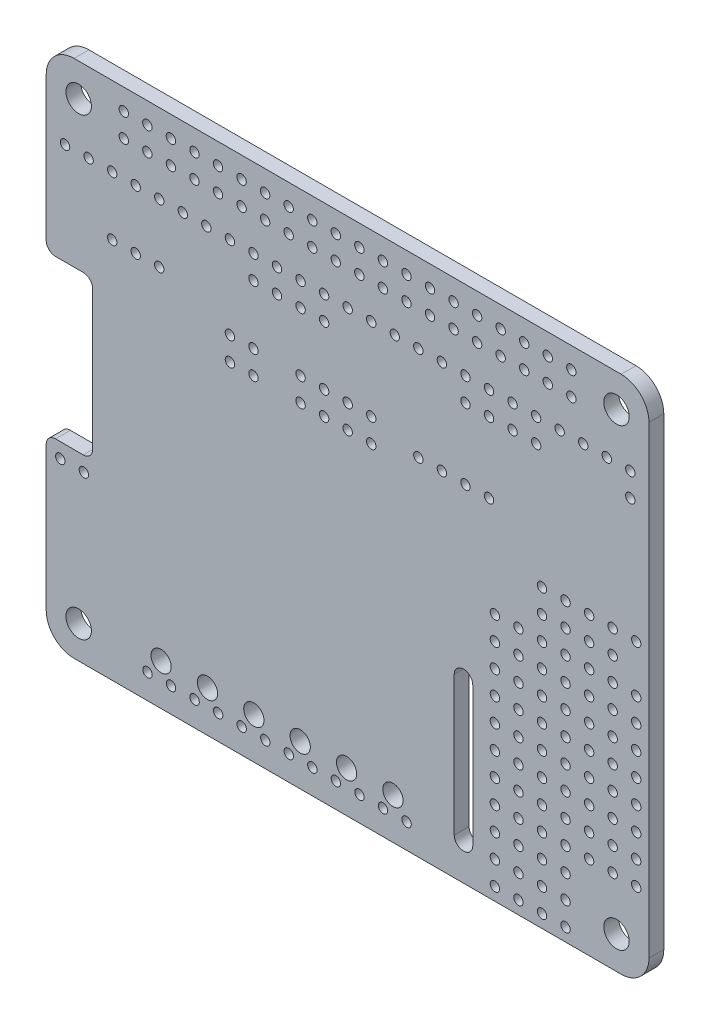
SolidWorks part; units mm, degrees
material "Polyethylene Cross-Linked"
ref_plane "Front Plane" through (0, 0, 0) normal (0, 0, 1) x (1, 0, 0)
ref_plane "Top Plane" through (0, 0, 0) normal (0, 1, 0) x (1, 0, 0)
ref_plane "Right Plane" through (0, 0, 0) normal (1, 0, 0) x (0, 0, -1)
sketch "Model" plane through (0, 0, 0) normal (0, 0, 1) x (1, 0, 0)
  line L16 (2.9997, 0) -> (62.0014, 0)
  line L17 (2.9997, 56.0332) -> (62.0014, 56.0332)
  line L18 (0, 2.9997) -> (0, 18.4988)
  line L19 (1.0008, 19.4996) -> (4.0005, 19.4996)
  line L20 (5.0013, 20.5003) -> (5.0013, 35.5329)
  line L21 (1.0008, 36.5336) -> (4.0005, 36.5336)
  line L22 (0, 37.5344) -> (0, 53.0335)
  line L23 (65.0011, 2.9997) -> (65.0011, 53.0335)
  line L24 (44.0004, 4.0005) -> (44.0004, 18.9992)
  line L25 (45.9994, 4.0005) -> (45.9994, 18.9992)
  arc A0 (0, 37.5344) -> (1.0008, 36.5336) centre (1.0008, 37.5344) ccw
  arc A1 (5.0013, 35.5329) -> (4.0005, 36.5336) centre (4.0005, 35.5329) ccw
  arc A2 (4.0005, 19.4996) -> (5.0013, 20.5003) centre (4.0005, 20.5003) ccw
  arc A3 (1.0008, 19.4996) -> (0, 18.4988) centre (1.0008, 18.4988) ccw
  arc A4 (2.9997, 56.0332) -> (0, 53.0335) centre (2.9997, 53.0335) ccw
  arc A5 (0, 2.9997) -> (2.9997, 0) centre (2.9997, 2.9997) ccw
  arc A6 (65.0011, 53.0335) -> (62.0014, 56.0332) centre (62.0014, 53.0335) ccw
  arc A7 (62.0014, 0) -> (65.0011, 2.9997) centre (62.0014, 2.9997) ccw
  arc A8 (44.0004, 4.0005) -> (45.9994, 4.0005) centre (44.9999, 4.0005) ccw
  arc A9 (45.9994, 18.9992) -> (44.0004, 18.9992) centre (44.9999, 18.9992) ccw
  circle A10 centre (8.3693, 53.7693) radius 0.508
  circle A11 centre (10.9093, 53.7693) radius 0.508
  circle A12 centre (13.4493, 53.7693) radius 0.508
  circle A13 centre (15.9893, 53.7693) radius 0.508
  circle A14 centre (18.5293, 53.7693) radius 0.508
  circle A15 centre (21.0693, 53.7693) radius 0.508
  circle A16 centre (23.6093, 53.7693) radius 0.508
  circle A17 centre (26.1493, 53.7693) radius 0.508
  circle A18 centre (28.6893, 53.7693) radius 0.508
  circle A19 centre (31.2293, 53.7693) radius 0.508
  circle A20 centre (33.7693, 53.7693) radius 0.508
  circle A21 centre (36.3093, 53.7693) radius 0.508
  circle A22 centre (38.8493, 53.7693) radius 0.508
  circle A23 centre (41.3893, 53.7693) radius 0.508
  circle A24 centre (43.9293, 53.7693) radius 0.508
  circle A25 centre (46.4693, 53.7693) radius 0.508
  circle A26 centre (49.0093, 53.7693) radius 0.508
  circle A27 centre (51.5493, 53.7693) radius 0.508
  circle A28 centre (54.0893, 53.7693) radius 0.508
  circle A29 centre (56.6293, 53.7693) radius 0.508
  circle A30 centre (10.9093, 51.2293) radius 0.508
  circle A31 centre (13.4493, 51.2293) radius 0.508
  circle A32 centre (15.9893, 51.2293) radius 0.508
  circle A33 centre (18.5293, 51.2293) radius 0.508
  circle A34 centre (21.0693, 51.2293) radius 0.508
  circle A35 centre (23.6093, 51.2293) radius 0.508
  circle A36 centre (26.1493, 51.2293) radius 0.508
  circle A37 centre (28.6893, 51.2293) radius 0.508
  circle A38 centre (31.2293, 51.2293) radius 0.508
  circle A39 centre (33.7693, 51.2293) radius 0.508
  circle A40 centre (36.3093, 51.2293) radius 0.508
  circle A41 centre (38.8493, 51.2293) radius 0.508
  circle A42 centre (41.3893, 51.2293) radius 0.508
  circle A43 centre (43.9293, 51.2293) radius 0.508
  circle A44 centre (46.4693, 51.2293) radius 0.508
  circle A45 centre (49.0093, 51.2293) radius 0.508
  circle A46 centre (51.5493, 51.2293) radius 0.508
  circle A47 centre (54.0893, 51.2293) radius 0.508
  circle A48 centre (56.6293, 51.2293) radius 0.508
  circle A49 centre (8.3693, 51.2293) radius 0.508
  circle A50 centre (3.5001, 52.4993) radius 1.3741
  circle A51 centre (61.4998, 52.4993) radius 1.3741
  circle A52 centre (61.4998, 3.5001) radius 1.3741
  circle A53 centre (3.5001, 3.5001) radius 1.3741
  circle A54 centre (2.032, 47.498) radius 0.508
  circle A55 centre (4.572, 47.498) radius 0.508
  circle A56 centre (7.112, 47.498) radius 0.508
  circle A57 centre (9.652, 47.498) radius 0.508
  circle A58 centre (12.192, 47.498) radius 0.508
  circle A59 centre (14.732, 47.498) radius 0.508
  circle A60 centre (17.272, 47.498) radius 0.508
  circle A61 centre (19.812, 47.498) radius 0.508
  circle A62 centre (22.352, 47.498) radius 0.508
  circle A63 centre (24.892, 47.498) radius 0.508
  circle A64 centre (27.432, 47.498) radius 0.508
  circle A65 centre (29.972, 47.498) radius 0.508
  circle A66 centre (32.512, 47.498) radius 0.508
  circle A67 centre (35.052, 47.498) radius 0.508
  circle A68 centre (37.592, 47.498) radius 0.508
  circle A69 centre (40.132, 47.498) radius 0.508
  circle A70 centre (42.672, 47.498) radius 0.508
  circle A71 centre (45.212, 47.498) radius 0.508
  circle A72 centre (47.752, 47.498) radius 0.508
  circle A73 centre (50.292, 47.498) radius 0.508
  circle A74 centre (52.832, 47.498) radius 0.508
  circle A75 centre (55.372, 47.498) radius 0.508
  circle A76 centre (57.912, 47.498) radius 0.508
  circle A77 centre (60.452, 47.498) radius 0.508
  circle A78 centre (62.992, 47.498) radius 0.508
  circle A79 centre (22.352, 44.958) radius 0.508
  circle A80 centre (24.892, 44.958) radius 0.508
  circle A81 centre (27.432, 44.958) radius 0.508
  circle A82 centre (29.972, 44.958) radius 0.508
  circle A83 centre (45.212, 44.958) radius 0.508
  circle A84 centre (47.752, 44.958) radius 0.508
  circle A85 centre (50.292, 44.958) radius 0.508
  circle A86 centre (52.832, 44.958) radius 0.508
  circle A87 centre (62.992, 44.958) radius 0.508
  circle A88 centre (4.064, 17.907) radius 0.508
  circle A89 centre (1.524, 17.907) radius 0.508
  circle A90 centre (38.862, 2.667) radius 0.508
  circle A91 centre (36.322, 2.667) radius 0.508
  circle A92 centre (33.782, 2.667) radius 0.508
  circle A93 centre (31.242, 2.667) radius 0.508
  circle A94 centre (28.702, 2.667) radius 0.508
  circle A95 centre (26.162, 2.667) radius 0.508
  circle A96 centre (23.622, 2.667) radius 0.508
  circle A97 centre (21.082, 2.667) radius 0.508
  circle A98 centre (18.542, 2.667) radius 0.508
  circle A99 centre (16.002, 2.667) radius 0.508
  circle A100 centre (13.462, 2.667) radius 0.508
  circle A101 centre (10.922, 2.667) radius 0.508
  circle A102 centre (37.3913, 4.445) radius 1.0922
  circle A103 centre (32.3926, 4.445) radius 1.0922
  circle A104 centre (27.3914, 4.445) radius 1.0922
  circle A105 centre (22.3926, 4.445) radius 1.0922
  circle A106 centre (17.3914, 4.445) radius 1.0922
  circle A107 centre (12.3927, 4.445) radius 1.0922
  circle A108 centre (48.387, 1.397) radius 0.508
  circle A109 centre (50.927, 1.397) radius 0.508
  circle A110 centre (53.467, 1.397) radius 0.508
  circle A111 centre (56.007, 1.397) radius 0.508
  circle A112 centre (50.927, 3.937) radius 0.508
  circle A113 centre (53.467, 3.937) radius 0.508
  circle A114 centre (56.007, 3.937) radius 0.508
  circle A115 centre (50.927, 6.477) radius 0.508
  circle A116 centre (53.467, 6.477) radius 0.508
  circle A117 centre (56.007, 6.477) radius 0.508
  circle A118 centre (50.927, 9.017) radius 0.508
  circle A119 centre (53.467, 9.017) radius 0.508
  circle A120 centre (56.007, 9.017) radius 0.508
  circle A121 centre (50.927, 11.557) radius 0.508
  circle A122 centre (53.467, 11.557) radius 0.508
  circle A123 centre (56.007, 11.557) radius 0.508
  circle A124 centre (50.927, 14.097) radius 0.508
  circle A125 centre (53.467, 14.097) radius 0.508
  circle A126 centre (56.007, 14.097) radius 0.508
  circle A127 centre (50.927, 16.637) radius 0.508
  circle A128 centre (53.467, 16.637) radius 0.508
  circle A129 centre (56.007, 16.637) radius 0.508
  circle A130 centre (50.927, 19.177) radius 0.508
  circle A131 centre (53.467, 19.177) radius 0.508
  circle A132 centre (56.007, 19.177) radius 0.508
  circle A133 centre (50.927, 21.717) radius 0.508
  circle A134 centre (53.467, 21.717) radius 0.508
  circle A135 centre (56.007, 21.717) radius 0.508
  circle A136 centre (50.927, 24.257) radius 0.508
  circle A137 centre (53.467, 24.257) radius 0.508
  circle A138 centre (56.007, 24.257) radius 0.508
  circle A139 centre (50.927, 26.797) radius 0.508
  circle A140 centre (53.467, 26.797) radius 0.508
  circle A141 centre (56.007, 26.797) radius 0.508
  circle A142 centre (48.387, 3.937) radius 0.508
  circle A143 centre (48.387, 6.477) radius 0.508
  circle A144 centre (48.387, 9.017) radius 0.508
  circle A145 centre (48.387, 11.557) radius 0.508
  circle A146 centre (48.387, 14.097) radius 0.508
  circle A147 centre (48.387, 16.637) radius 0.508
  circle A148 centre (48.387, 19.177) radius 0.508
  circle A149 centre (48.387, 21.717) radius 0.508
  circle A150 centre (48.387, 24.257) radius 0.508
  circle A151 centre (48.387, 26.797) radius 0.508
  circle A152 centre (58.547, 9.017) radius 0.508
  circle A153 centre (58.547, 11.557) radius 0.508
  circle A154 centre (58.547, 14.097) radius 0.508
  circle A155 centre (58.547, 16.637) radius 0.508
  circle A156 centre (58.547, 19.177) radius 0.508
  circle A157 centre (58.547, 21.717) radius 0.508
  circle A158 centre (58.547, 24.257) radius 0.508
  circle A159 centre (58.547, 26.797) radius 0.508
  circle A160 centre (61.087, 9.017) radius 0.508
  circle A161 centre (61.087, 11.557) radius 0.508
  circle A162 centre (61.087, 14.097) radius 0.508
  circle A163 centre (61.087, 16.637) radius 0.508
  circle A164 centre (61.087, 19.177) radius 0.508
  circle A165 centre (61.087, 21.717) radius 0.508
  circle A166 centre (61.087, 24.257) radius 0.508
  circle A167 centre (61.087, 26.797) radius 0.508
  circle A168 centre (63.627, 9.017) radius 0.508
  circle A169 centre (63.627, 11.557) radius 0.508
  circle A170 centre (63.627, 14.097) radius 0.508
  circle A171 centre (63.627, 16.637) radius 0.508
  circle A172 centre (63.627, 19.177) radius 0.508
  circle A173 centre (63.627, 21.717) radius 0.508
  circle A174 centre (63.627, 24.257) radius 0.508
  circle A175 centre (63.627, 26.797) radius 0.508
  circle A176 centre (61.087, 29.337) radius 0.508
  circle A177 centre (58.547, 29.337) radius 0.508
  circle A178 centre (56.007, 29.337) radius 0.508
  circle A179 centre (53.467, 29.337) radius 0.508
  circle A180 centre (61.087, 31.877) radius 0.508
  circle A181 centre (58.547, 31.877) radius 0.508
  circle A182 centre (56.007, 31.877) radius 0.508
  circle A183 centre (53.467, 31.877) radius 0.508
  circle A184 centre (63.627, 31.877) radius 0.508
  circle A185 centre (47.752, 37.338) radius 0.508
  circle A186 centre (45.212, 37.338) radius 0.508
  circle A188 centre (42.672, 37.338) radius 0.508
  circle A189 centre (40.132, 37.338) radius 0.508
  circle A190 centre (35.052, 38.608) radius 0.508
  circle A191 centre (35.052, 36.068) radius 0.508
  circle A192 centre (32.512, 36.068) radius 0.508
  circle A193 centre (32.512, 38.608) radius 0.508
  circle A194 centre (29.972, 38.608) radius 0.508
  circle A195 centre (29.972, 36.068) radius 0.508
  circle A196 centre (27.432, 36.068) radius 0.508
  circle A197 centre (27.432, 38.608) radius 0.508
  circle A198 centre (22.352, 38.608) radius 0.508
  circle A199 centre (22.352, 36.068) radius 0.508
  circle A200 centre (19.812, 36.068) radius 0.508
  circle A201 centre (19.812, 38.608) radius 0.508
  circle A202 centre (12.192, 41.148) radius 0.508
  circle A203 centre (9.652, 41.148) radius 0.508
  circle A204 centre (7.112, 41.148) radius 0.508
  dimension "D1" = 1.0008
  dimension "D2" = 2.9997
  dimension "D3" = 5.0013
  dimension "D7" = 1.016
  dimension "D14" = 2.7483
  dimension "D19" = 1.016
  dimension "D24" = 1.016
  dimension "D4" = 62.0014
  dimension "D5" = 19.4996
  dimension "D6" = 4
  dimension "D8" = 8.3693
  dimension "D9" = 11
  dimension "D12" = 2.54
  dimension "D13" = 2.54
  dimension "D15" = 3.5001
  dimension "D16" = 61.4998
  dimension "D17" = 3.5001
  dimension "D18" = 52.4993
  dimension "D20" = 2.032
  dimension "D21" = 2.264
  dimension "D23" = 2.54
  dimension "D25" = 8.5352
  dimension "D26" = 2.54
  dimension "D10" = 20
  dimension "D11" = 2
  dimension "D22" = 25
  dimension "D27" = 4
  dimension "D28" = 3
  dimension "D29" = 2
extrude "Boss-Extrude1" add sketch "Model" along normal blind 1.6002
